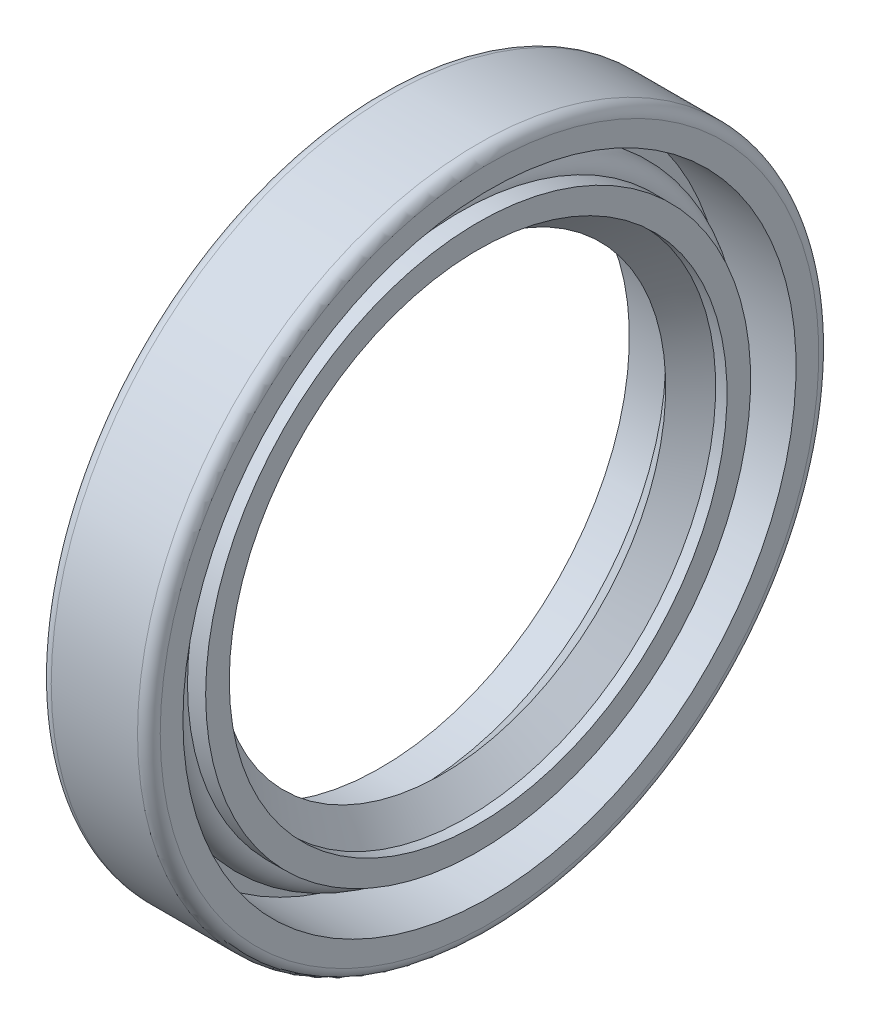
SolidWorks part; units mm, degrees
material "Rubber"
ref_plane "Front Plane" through (0, 0, 0) normal (0, 0, 1) x (1, 0, 0)
ref_plane "Top Plane" through (0, 0, 0) normal (0, 1, 0) x (1, 0, 0)
ref_plane "Right Plane" through (0, 0, 0) normal (1, 0, 0) x (0, 0, -1)
sketch "Sketch1" plane through (0, 0, 0) normal (0, 0, 1) x (1, 0, 0)
  line L0 (-23.4257, -8.0654) -> (-17.3297, -8.0654) construction
  line L1 (-23.4257, 5.8538) -> (-21.3937, 5.8538)
  line L2 (-21.3937, 7.1746) -> (-21.0127, 7.1746)
  line L4 (-21.3937, 9.0796) -> (-17.3297, 9.0796)
  line L6 (-23.4257, 5.8538) -> (-23.4257, 9.0796)
  line L7 (-21.3937, 7.1746) -> (-21.3937, 9.0796)
  line L8 (-17.9647, 5.8538) -> (-17.9647, 7.1746)
  line L9 (-17.3297, 10.9846) -> (-23.4257, 10.9846)
  line L10 (-25.6025, 4.4568) -> (-13.5321, 4.4568) construction
  line L11 (-23.4257, 10.9846) -> (-23.4257, 9.0796)
  line L12 (-17.3297, 10.9846) -> (-17.3297, 9.0796)
  line L13 (-21.3937, 7.1746) -> (-21.3937, 5.8538) construction
  line L14 (-17.9647, 7.1746) -> (-17.3297, 7.1746) construction
  line L15 (-17.3297, 9.0796) -> (-17.3297, 7.1746) construction
  line L16 (-21.3937, 4.4568) -> (-21.3937, -1.3343) construction
  line L17 (-21.3937, 5.8538) -> (-19.9967, 4.4568)
  line L18 (-19.9967, 4.4568) -> (-18.5997, 5.8538)
  line L20 (-18.9807, 7.1746) -> (-17.9647, 7.1746)
  line L21 (-18.5997, 5.8538) -> (-17.9647, 5.8538)
  arc A0 (-21.0127, 7.1746) -> (-18.9807, 7.1746) centre (-19.9967, 7.1746) cw
  point P22 (0, 0)
  point P23 (0, 0)
  point P24 (0, 0)
  point P25 (0, 0)
  point P26 (0, 0)
  point P27 (0, 0)
  point P28 (0, 0)
  point P29 (0, 0)
  dimension "D7" = 1.016
  dimension "D1" = 12.5222
  dimension "D2" = 13.9192
  dimension "D3" = 17.145
  dimension "D4" = 19.05
  dimension "D5" = 6.096
  dimension "D6" = 2.032
  dimension "D8" = 135
  dimension "D9" = 135
revolve "Revolve1" add sketch "Sketch1" angle 360 about L0
fillet "Fillet1" radius 0.635 2 edges at (-17.3297, -8.0654, 19.05) (-23.4257, -8.0654, 19.05)
